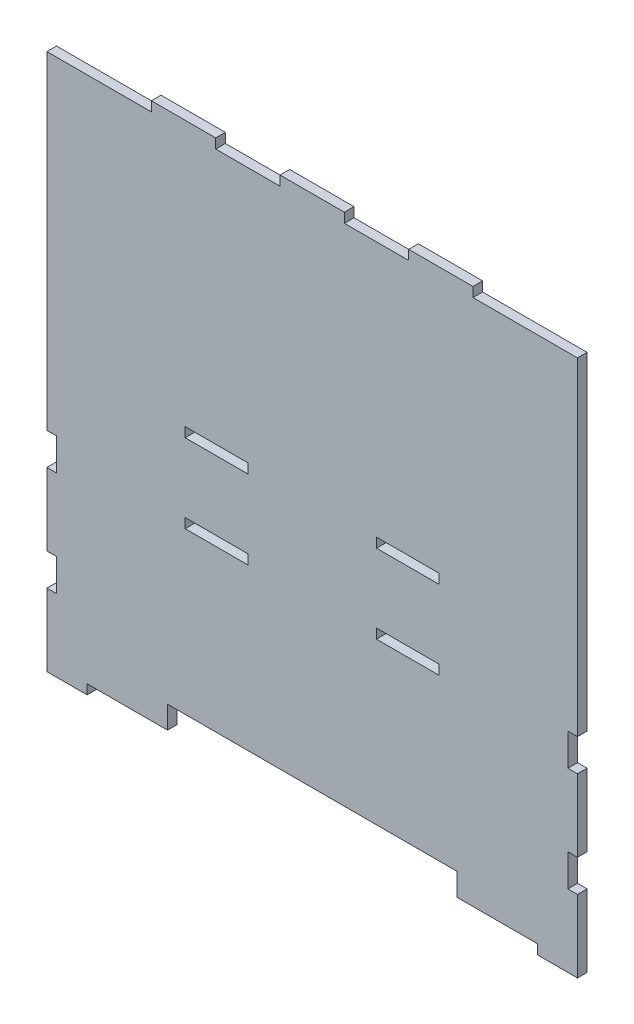
SolidWorks part; units mm, degrees
ref_plane "Plan de face" through (0, 0, 0) normal (0, 0, 1) x (1, 0, 0)
ref_plane "Plan de dessus" through (0, 0, 0) normal (0, 1, 0) x (1, 0, 0)
ref_plane "Plan de droite" through (0, 0, 0) normal (1, 0, 0) x (0, 0, -1)
sketch "Esquisse1" plane through (0, 0, 0) normal (0, 0, 1) x (1, 0, 0)
  line L1 (0, 0) -> (-330, 0)
  line L2 (0, 0) -> (0, 340)
  line L3 (0, 340) -> (-330, 340)
  line L4 (-330, 0) -> (-330, 340)
  dimension "D1" = 340
  dimension "D2" = 330
extrude "Boss.-Extru.1" add sketch "Esquisse1" along normal blind 6
sketch "Esquisse2" plane through (0, 0, 6) normal (0, 0, 1) x (1, 0, 0)
  line L1 (0, 340) -> (-330, 340) construction
  line L2 (-244, 175) -> (-205, 175)
  line L3 (-244, 175) -> (-244, 169)
  line L4 (-244, 169) -> (-205, 169)
  line L6 (-205, 175) -> (-205, 169)
  line L7 (-125, 175) -> (-86, 175)
  line L8 (-125, 175) -> (-125, 169)
  line L9 (-125, 169) -> (-86, 169)
  line L10 (-330, 340) -> (-330, 0) construction
  line L11 (-330, 130) -> (-324, 130)
  line L12 (-330, 130) -> (-330, 110)
  line L13 (-330, 110) -> (-324, 110)
  line L14 (-324, 130) -> (-324, 110)
  line L15 (0, 0) -> (0, 340) construction
  line L16 (-330, 65) -> (-324, 65)
  line L17 (-330, 65) -> (-330, 45)
  line L18 (-330, 45) -> (-324, 45)
  line L19 (-324, 65) -> (-324, 45)
  line L20 (0, 130) -> (-6, 130)
  line L21 (0, 130) -> (0, 110)
  line L22 (0, 110) -> (-6, 110)
  line L23 (-6, 130) -> (-6, 110)
  line L24 (-330, 0) -> (0, 0) construction
  line L25 (0, 65) -> (-6, 65)
  line L26 (0, 65) -> (0, 45)
  line L27 (0, 45) -> (-6, 45)
  line L28 (-6, 65) -> (-6, 45)
  line L29 (-86, 175) -> (-86, 169)
  line L30 (-244, 126) -> (-205, 126)
  line L31 (-244, 126) -> (-244, 120)
  line L32 (-244, 120) -> (-205, 120)
  line L33 (-205, 126) -> (-205, 120)
  line L34 (-125, 126) -> (-86, 126)
  line L35 (-125, 126) -> (-125, 120)
  line L36 (-125, 120) -> (-86, 120)
  line L37 (-86, 126) -> (-86, 120)
  line L38 (-330, 340) -> (-265, 340)
  line L39 (-330, 340) -> (-330, 334)
  line L40 (-330, 334) -> (-265, 334)
  line L41 (-265, 340) -> (-265, 334)
  line L42 (-225, 340) -> (-185, 340)
  line L43 (-225, 340) -> (-225, 334)
  line L44 (-225, 334) -> (-185, 334)
  line L45 (-185, 340) -> (-185, 334)
  line L47 (-145, 340) -> (-105, 340)
  line L48 (-145, 340) -> (-145, 334)
  line L49 (-145, 334) -> (-105, 334)
  line L50 (-105, 340) -> (-105, 334)
  line L51 (0, 340) -> (-65, 340)
  line L52 (0, 340) -> (0, 334)
  line L53 (0, 334) -> (-65, 334)
  line L54 (-65, 340) -> (-65, 334)
  line L55 (-305, 0) -> (-255, 0)
  line L56 (-305, 0) -> (-305, 6)
  line L57 (-305, 6) -> (-255, 6)
  line L59 (-255, 0) -> (-75, 0)
  line L60 (-255, 6) -> (-255, 20)
  line L61 (-255, 20) -> (-75, 20)
  line L62 (-75, 6) -> (-75, 20)
  line L63 (-75, 0) -> (-25, 0)
  line L65 (-75, 6) -> (-25, 6)
  line L66 (-25, 0) -> (-25, 6)
  dimension "D1" = 20
  dimension "D2" = 6
  dimension "D3" = 6
  dimension "D4" = 20
  dimension "D5" = 45
  dimension "D6" = 45
  dimension "D7" = 20
  dimension "D8" = 6
  dimension "D9" = 20
  dimension "D10" = 6
  dimension "D11" = 45
  dimension "D12" = 45
  dimension "D13" = 6
  dimension "D14" = 39
  dimension "D15" = 6
  dimension "D16" = 39
  dimension "D17" = 39
  dimension "D18" = 6
  dimension "D19" = 6
  dimension "D20" = 39
  dimension "D21" = 86
  dimension "D22" = 80
  dimension "D23" = 80
  dimension "D24" = 86
  dimension "D25" = 175
  dimension "D26" = 126
  dimension "D27" = 126
  dimension "D28" = 175
  dimension "D29" = 65
  dimension "D30" = 6
  dimension "D31" = 6
  dimension "D32" = 40
  dimension "D33" = 40
  dimension "D34" = 40
  dimension "D35" = 6
  dimension "D36" = 40
  dimension "D37" = 40
  dimension "D38" = 6
  dimension "D39" = 6
  dimension "D40" = 20
  dimension "D41" = 6
  dimension "D42" = 25
  dimension "D43" = 50
  dimension "D44" = 180
  dimension "D45" = 25
extrude "Enlèv. mat encoche" cut sketch "Esquisse2" against normal through all
